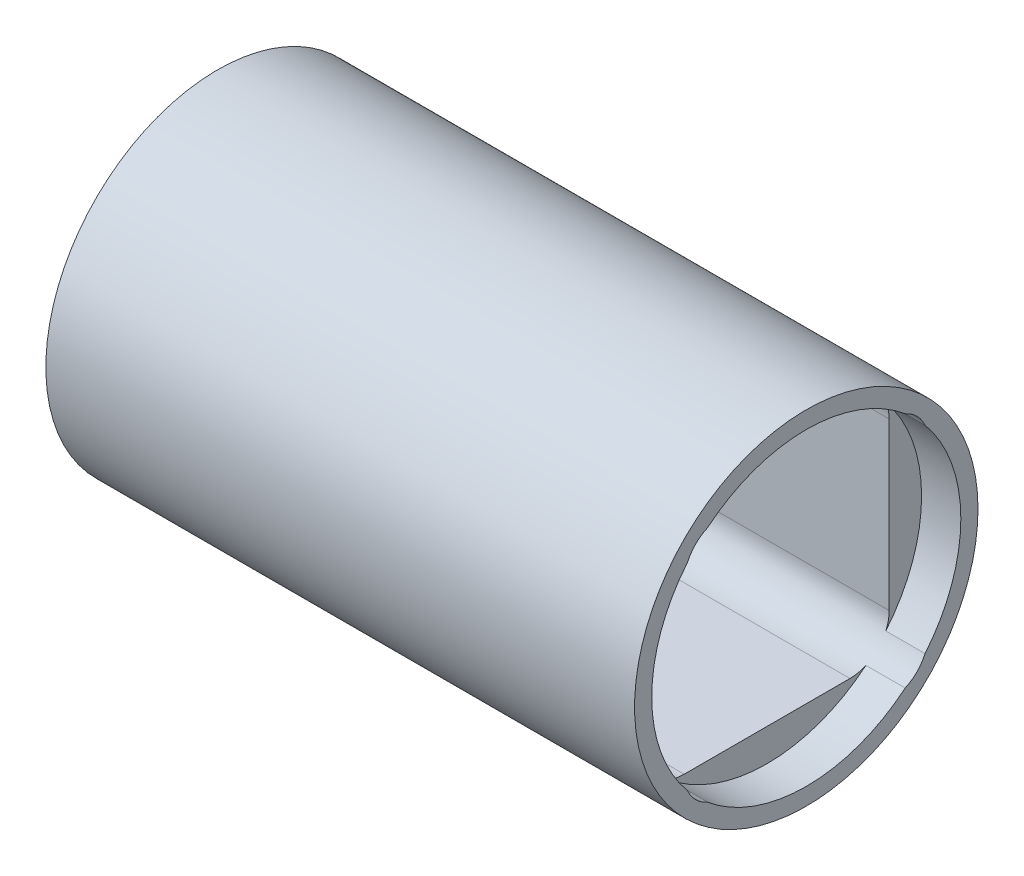
SolidWorks part; units mm, degrees
material "Plain Carbon Steel"
ref_plane "Front Plane" through (0, 0, 0) normal (0, 0, 1) x (1, 0, 0)
ref_plane "Top Plane" through (0, 0, 0) normal (0, 1, 0) x (1, 0, 0)
ref_plane "Right Plane" through (0, 0, 0) normal (1, 0, 0) x (0, 0, -1)
sketch "Sketch1" plane through (0, 0, 0) normal (0, 0, 1) x (1, 0, 0)
  line L0 (0, 0) -> (0, 17.5)
  line L1 (0, 17.5) -> (60, 17.5)
  line L2 (60, 17.5) -> (60, 0)
  line L3 (60, 0) -> (0, 0)
  line L4 (0, 0) -> (-29.537, 0) construction
  dimension "D1" = 35
  dimension "D2" = 60
revolve "Revolve1" add sketch "Sketch1" angle 360 about L4
sketch "Sketch3" plane through (60, 0, 0) normal (1, 0, 0) x (0, 0, -1)
  circle A0 centre (0, 0) radius 15.75
  dimension "D1" = 31.5
extrude "Cut-Extrude1" cut sketch "Sketch3" against normal blind 4
sketch "Sketch4" plane through (56, 0, 0) normal (1, 0, 0) x (0, 0, -1)
  line L0 (-8.45, 12.45) -> (8.45, 12.45)
  line L1 (-12.45, 8.45) -> (-12.45, -8.45)
  line L2 (12.45, 8.45) -> (12.45, -8.45)
  line L3 (-8.45, -12.45) -> (8.45, -12.45)
  line L4 (-12.45, 12.45) -> (12.45, -12.45) construction
  line L5 (12.45, 12.45) -> (-12.45, -12.45) construction
  arc A0 (-12.45, 8.45) -> (-8.45, 12.45) centre (-8.45, 8.45) cw
  arc A1 (-12.45, -8.45) -> (-8.45, -12.45) centre (-8.45, -8.45) ccw
  arc A2 (12.45, -8.45) -> (8.45, -12.45) centre (8.45, -8.45) cw
  arc A3 (8.45, 12.45) -> (12.45, 8.45) centre (8.45, 8.45) cw
  point P1 (0, 0)
  dimension "D1" = 4
  dimension "D2" = 24.9
extrude "Cut-Extrude2" cut sketch "Sketch4" against normal blind 25 and the other way blind 25
sketch "Sketch5" plane through (0, 0, 0) normal (-1, 0, 0) x (0, 0, 1)
  circle A0 centre (0, 0) radius 6
  dimension "D1" = 12
extrude "Cut-Extrude3" cut sketch "Sketch5" against normal through all
sketch "Sketch6" plane through (0, 0, 0) normal (-1, 0, 0) x (0, 0, 1)
  line L0 (-2, 8) -> (-2, 4)
  line L1 (-2, 8) -> (2, 8)
  line L2 (-2, 4) -> (2, 4)
  line L3 (2, 8) -> (2, 4)
  line L4 (-2, 8) -> (2, 4) construction
  line L5 (-2, 4) -> (2, 8) construction
  line L6 (0, 0) -> (0, 6) construction
  circle A0 centre (0, 0) radius 6 construction
  point P1 (0, 6)
  dimension "D1" = 4
extrude "Cut-Extrude5" cut sketch "Sketch6" against normal through all
